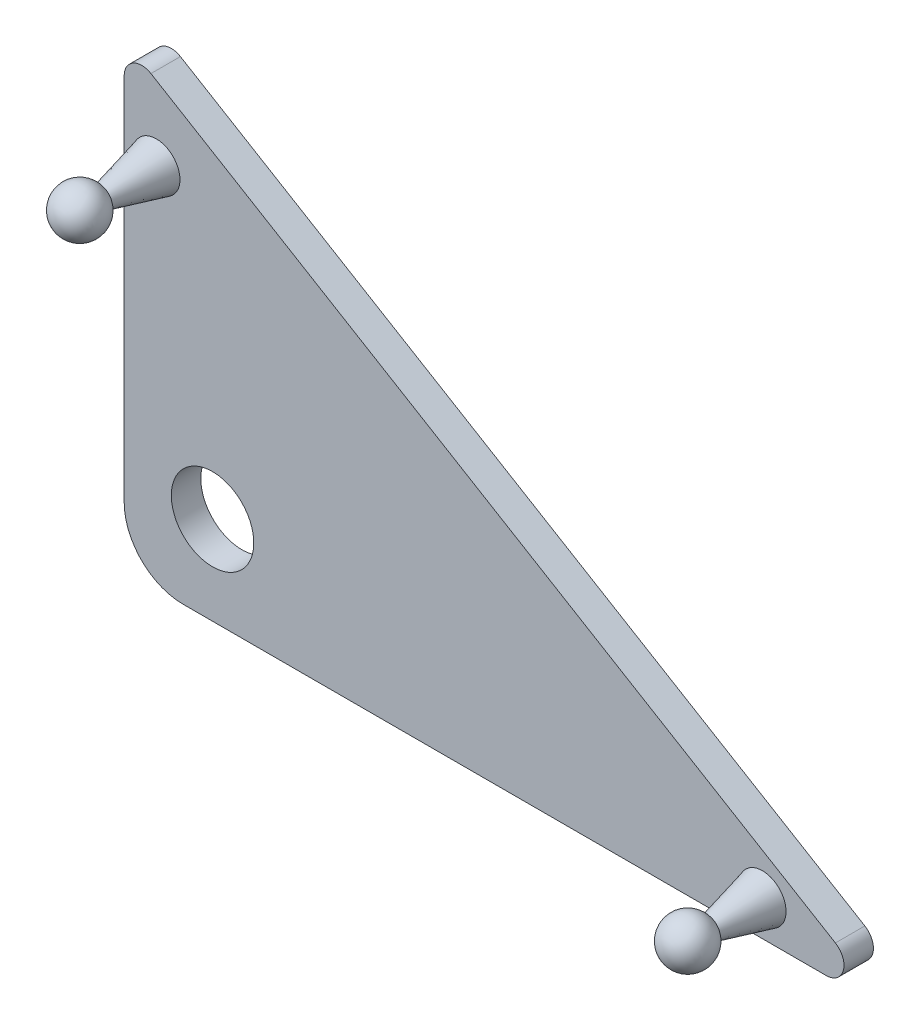
SolidWorks part; units mm, degrees
material "201.0-T6, per stampo in conchiglia (SS)"
ref_plane "Piano frontale" through (0, 0, 0) normal (0, 0, 1) x (1, 0, 0)
ref_plane "Piano superiore" through (0, 0, 0) normal (0, 1, 0) x (1, 0, 0)
ref_plane "Piano destro" through (0, 0, 0) normal (1, 0, 0) x (0, 0, -1)
sketch "Schizzo1" plane through (0, 0, 0) normal (0, 0, 1) x (1, 0, 0)
  line L0 (0, 0) -> (0, 78)
  line L1 (0, 78) -> (130, 0)
  line L2 (130, 0) -> (0, 0)
  dimension "D1" = 78
  dimension "D2" = 130
extrude "Estrusione-Estrusione1" add sketch "Schizzo1" along normal blind 5
sketch "Schizzo2" plane through (0, 0, 0) normal (0, 0, -1) x (-1, 0, 0)
  line L0 (0, 78) -> (0, 0) construction
  line L1 (0, 0) -> (-130, 0) construction
  circle A0 centre (-15, 15) radius 7
  dimension "D1" = 15
  dimension "D2" = 15
extrude "Taglio-Estrusione1" cut sketch "Schizzo2" against normal through all
fillet "Raccordo1" radius 10 1 edges at (0, 0, 2.5)
sketch "Schizzo3" plane through (0, 0, 5) normal (0, 0, 1) x (1, 0, 0)
  circle A0 centre (5.464, 62.1376) radius 4
extrude "Estrusione-Estrusione2" add sketch "Schizzo3" along normal blind 10 draft 14
sketch "Schizzo4" plane through (0, 0, 15) normal (0, 0, 1) x (1, 0, 0)
  point P0 (5.464, 62.1376)
ref_plane "Piano1" through (0, 62.1376, 0) normal (0, 1, 0) x (1, 0, 0)
sketch "Schizzo5" plane through (0, 62.1376, 0) normal (0, 1, 0) x (1, 0, 0)
  line L0 (9.464, -18) -> (1.464, -18)
  line L1 (3.9573, -15) -> (6.9707, -15) construction
  arc A0 (1.464, -18) -> (9.464, -18) centre (5.464, -18) ccw
  dimension "D2" = 3
  dimension "D1" = 8
  dimension "D3" = 0
revolve "Rivoluzione1" add sketch "Schizzo5" angle 360 about L0
fillet "Raccordo2" radius 3 2 edges at (130, 0, 2.5) (0, 78, 2.5)
sketch "Schizzo6" plane through (0, 0, 5) normal (0, 0, 1) x (1, 0, 0)
  line L0 (120.7125, 5.5725) -> (4.5435, 75.2739) construction
  line L1 (10, 0) -> (119.169, 0) construction
  circle A0 centre (108.3381, 6) radius 4
  dimension "D1" = 6
  dimension "D2" = 6
extrude "Estrusione-Estrusione3" add sketch "Schizzo6" along normal blind 10 draft 14
sketch "Schizzo7" plane through (0, 0, 15) normal (0, 0, 1) x (1, 0, 0)
  point P0 (108.3381, 6)
ref_plane "Piano3" through (0, 6, 0) normal (0, 1, 0) x (1, 0, 0)
sketch "Schizzo9" plane through (0, 6, 0) normal (0, 1, 0) x (1, 0, 0)
  line L0 (112.3381, -17.6941) -> (104.3381, -17.6941)
  arc A0 (112.3381, -17.6941) -> (104.3381, -17.6941) centre (108.3381, -17.6941) cw
  dimension "D1" = 8
  dimension "D2" = 0
revolve "Rivoluzione3" add sketch "Schizzo9" angle 360 about L0
